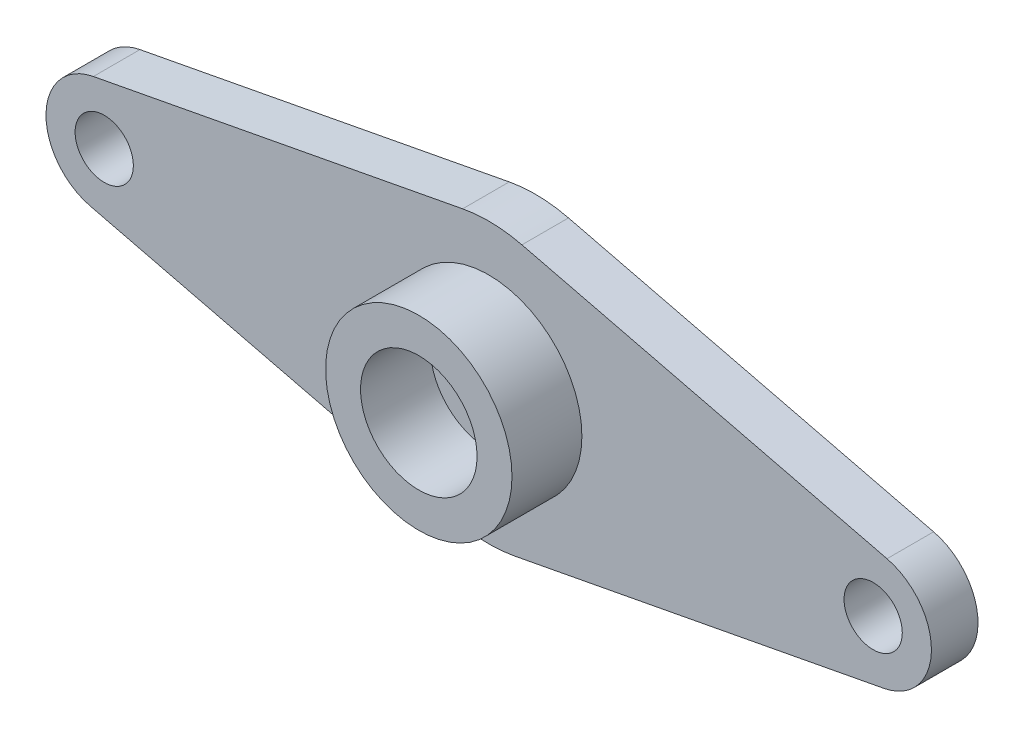
SolidWorks part; units mm, degrees
ref_plane "Front Plane" through (0, 0, 0) normal (0, 0, 1) x (1, 0, 0)
ref_plane "Top Plane" through (0, 0, 0) normal (0, 1, 0) x (1, 0, 0)
ref_plane "Right Plane" through (0, 0, 0) normal (1, 0, 0) x (0, 0, -1)
sketch "Sketch1" plane through (0, 0, 0) normal (0, 0, 1) x (1, 0, 0)
  line L0 (-16.5, 0.4326) -> (16.5, -0.4326) construction
  line L1 (-16.9659, 2.8888) -> (-1.1182, 5.8949)
  line L2 (1.4255, 5.8282) -> (17.094, 1.9958)
  line L3 (-1.4255, -5.8282) -> (-17.094, -1.9958)
  line L4 (16.9659, -2.8888) -> (1.1182, -5.8949)
  arc A0 (-1.4255, -5.8282) -> (1.1182, -5.8949) centre (0, 0) ccw
  arc A1 (-16.9659, 2.8888) -> (-17.094, -1.9958) centre (-16.5, 0.4326) ccw
  arc A2 (16.9659, -2.8888) -> (17.094, 1.9958) centre (16.5, -0.4326) ccw
  arc A3 (1.4255, 5.8282) -> (-1.1182, 5.8949) centre (0, 0) ccw
  circle A4 centre (-16.5, 0.4326) radius 1.25
  circle A5 centre (16.5, -0.4326) radius 1.25
  circle A6 centre (0, 0) radius 1.25
  point P5 (0, 0)
  dimension "D1" = 12
  dimension "D2" = 2.5
  dimension "D3" = 38
  dimension "D4" = 2.5
  dimension "D5" = 2.5
  dimension "D6" = 2.5
extrude "Boss-Extrude1" add sketch "Sketch1" along normal blind 2
sketch "Sketch2" plane through (0, 0, 2) normal (0, 0, 1) x (1, 0, 0)
  circle A0 centre (0, 0) radius 4
  circle A1 centre (0, 0) radius 2.5
  dimension "D1" = 8
  dimension "D2" = 5
extrude "Boss-Extrude2" add sketch "Sketch2" along normal blind 3
